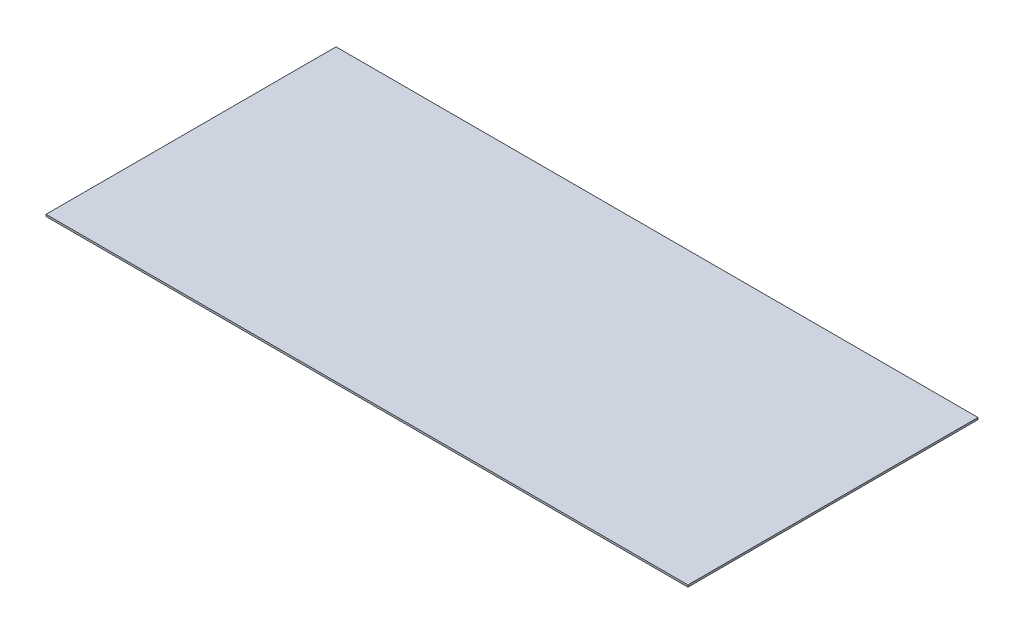
SolidWorks part; units mm, degrees
ref_plane "Front Plane" through (0, 0, 0) normal (0, 0, 1) x (1, 0, 0)
ref_plane "Top Plane" through (0, 0, 0) normal (0, 1, 0) x (1, 0, 0)
ref_plane "Right Plane" through (0, 0, 0) normal (1, 0, 0) x (0, 0, -1)
sketch "Sketch1" plane through (0, 0, 0) normal (0, 1, 0) x (1, 0, 0)
  line L1 (0, 0) -> (166, 0)
  line L2 (0, 0) -> (0, 75)
  line L3 (0, 75) -> (166, 75)
  line L4 (166, 0) -> (166, 75)
  dimension "D1" = 166
  dimension "D2" = 75
extrude "Boss-Extrude1" add sketch "Sketch1" along normal blind 0.5
